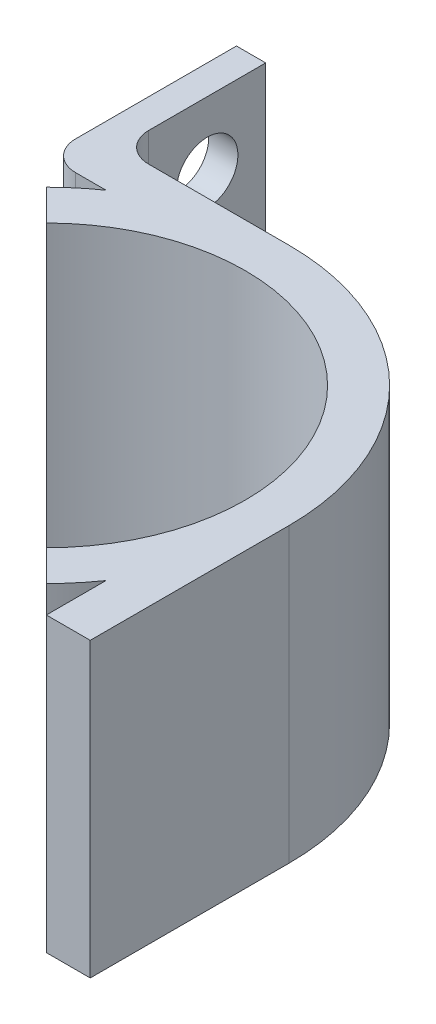
SolidWorks part; units mm, degrees
ref_plane "前视基准面" through (0, 0, 0) normal (0, 0, 1) x (1, 0, 0)
ref_plane "上视基准面" through (0, 0, 0) normal (0, 1, 0) x (1, 0, 0)
ref_plane "右视基准面" through (0, 0, 0) normal (1, 0, 0) x (0, 0, -1)
other "Configuration Table"
sketch "草图1" plane through (0, 0, 0) normal (0, 1, 0) x (1, 0, 0)
  line L3 (-16.6, -4.1781) -> (-30.2, -4.1781)
  line L4 (-30.2, -4.1781) -> (-30.2, -7.1781)
  line L5 (-30.2, -7.1781) -> (-26.1184, -7.1781)
  line L6 (-3, -30.2965) -> (-3, -34.3781)
  line L8 (0, -20.7781) -> (0, -34.3781)
  line L9 (0, -34.3781) -> (-3, -34.3781)
  line L12 (-26.2167, -11.1614) -> (-28.338, -9.0401)
  line L13 (-6.9833, -30.3947) -> (-4.862, -32.516)
  arc A0 (-16.6, -7.1781) -> (-3, -20.7781) centre (-16.6, -20.7781) cw
  arc A1 (0, -20.7781) -> (-16.6, -4.1781) centre (-16.6, -20.7781) ccw
  arc A2 (-5.4578, -28.5763) -> (-24.3982, -9.6359) centre (-16.6, -20.7781) ccw
  arc A3 (0, -20.7781) -> (-16.6, -4.1781) centre (-16.6, -20.7781) ccw
  arc A4 (-6.9833, -30.3947) -> (-26.2167, -11.1614) centre (-16.6, -20.7781) ccw
  arc A5 (-4.862, -32.516) -> (-3, -30.2965) centre (-16.6, -20.7781) ccw
  arc A6 (-26.1184, -7.1781) -> (-28.338, -9.0401) centre (-16.6, -20.7781) ccw
  arc A7 (0, -20.7781) -> (-16.6, -4.1781) centre (-16.6, -20.7781) ccw
  dimension "D1" = 13.6
  dimension "D2" = 3
  dimension "D5" = 13.6
  dimension "D3" = 3
  dimension "D4" = 13.6
extrude "凸台-拉伸2" add sketch "草图1" along normal blind 20
sketch "草图2" plane through (0, 20, 0) normal (0, 1, 0) x (1, 0, 0)
  line L0 (-30.2, -4.1781) -> (-30.2, 5.8219)
  line L1 (-30.2, 5.8219) -> (-28.2, 5.8219)
  line L2 (-28.2, 5.8219) -> (-28.2, -4.1781)
  line L3 (-16.6, -4.1781) -> (-30.2, -4.1781) construction
  line L4 (-28.2, -4.1781) -> (-30.2, -4.1781)
  dimension "D1" = 2
  dimension "D2" = 10
extrude "凸台-拉伸3" add sketch "草图2" against normal blind 20
fillet "圆角1" radius 2 1 edges at (-28.2, 10, 4.1781)
sketch "草图3" plane through (-28.2, 0, 0) normal (1, 0, 0) x (0, 0, -1)
  line L0 (5.8219, 0) -> (5.8219, 20) construction
  line L1 (-2.1781, 20) -> (5.8219, 20) construction
  line L2 (-2.1781, 0) -> (5.8219, 0) construction
  circle A0 centre (1.8219, 15.5) radius 2.1
  circle A1 centre (1.8219, 4.5) radius 2.1
  dimension "D1" = 4.2
  dimension "D2" = 4.2
  dimension "D3" = 4
  dimension "D4" = 4
  dimension "D5" = 4.5
  dimension "D6" = 4.5
extrude "切除-拉伸1" cut sketch "草图3" against normal blind 20
fillet "圆角2" radius 2 1 edges at (-30.2, 10, 7.1781)
